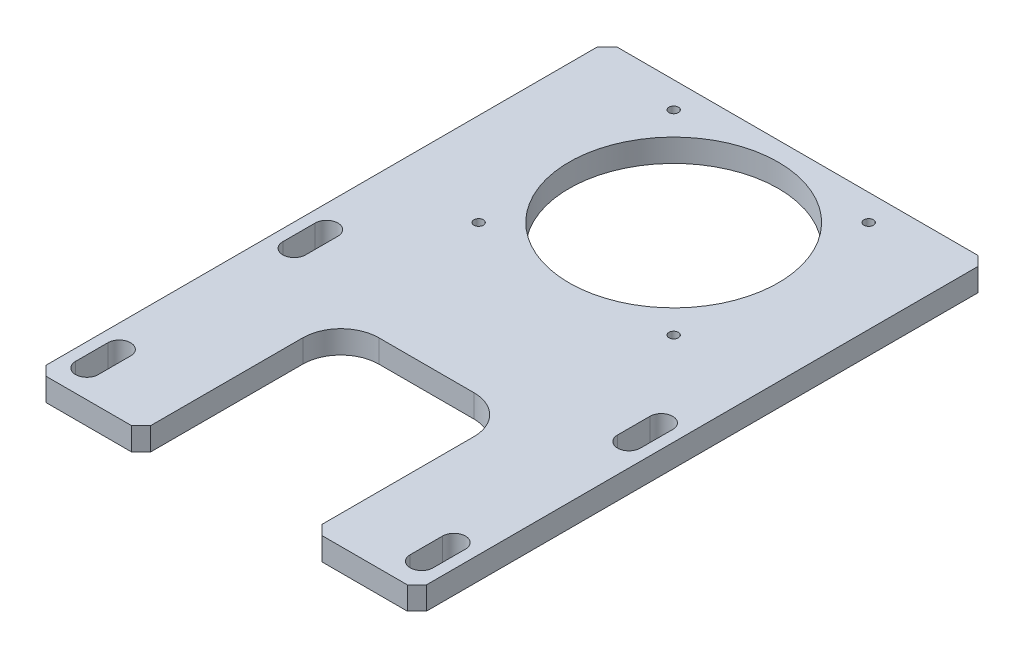
SolidWorks part; units mm, degrees
ref_plane "Front" through (0, 0, 0) normal (0, 0, 1) x (1, 0, 0)
ref_plane "Top" through (0, 0, 0) normal (0, 1, 0) x (1, 0, 0)
ref_plane "Right" through (0, 0, 0) normal (1, 0, 0) x (0, 0, -1)
sketch "Sketch1" plane through (0, 0, 0) normal (0, 1, 0) x (1, 0, 0)
  line L0 (0, 14.9989) -> (0, -319.3105) construction
  line L1 (-100, 0) -> (100, 0)
  line L2 (-100, 0) -> (-100, -300)
  line L3 (-100, -300) -> (100, -300)
  line L4 (100, 0) -> (100, -300)
  dimension "D1" = 200
  dimension "D2" = 300
extrude "Boss-Extrude1" add sketch "Sketch1" along normal blind 12
sketch "Sketch2" plane through (0, 12, 0) normal (0, 1, 0) x (1, 0, 0)
  line L0 (-100, -300) -> (100, -300) construction
  line L1 (-45, -195) -> (45, -195)
  line L2 (-45, -195) -> (-45, -300)
  line L3 (-45, -300) -> (45, -300)
  line L4 (45, -195) -> (45, -300)
  line L5 (0, 22.6259) -> (0, -270.9785) construction
  line L6 (100, 0) -> (-100, 0) construction
  dimension "D1" = 90
  dimension "D2" = 195
extrude "Cut-Extrude1" cut sketch "Sketch2" against normal up to next
sketch "Sketch3" plane through (0, 12, 0) normal (0, 1, 0) x (1, 0, 0)
  line L0 (100, 0) -> (-100, 0) construction
  circle A0 centre (0, -65) radius 55
  dimension "D1" = 110
  dimension "D2" = 65
extrude "Cut-Extrude2" cut sketch "Sketch3" against normal up to next
sketch "Sketch4" plane through (0, 12, 0) normal (0, 1, 0) x (1, 0, 0)
  line L0 (-88, -268.5) -> (-88, -285.5) construction
  line L1 (-82, -268.5) -> (-82, -285.5)
  line L2 (-94, -268.5) -> (-94, -285.5)
  line L3 (88, -268.5) -> (88, -285.5) construction
  line L4 (94, -268.5) -> (94, -285.5)
  line L5 (82, -268.5) -> (82, -285.5)
  line L6 (-88, -176.5) -> (-88, -159.5) construction
  line L7 (-94, -176.5) -> (-94, -159.5)
  line L8 (-82, -176.5) -> (-82, -159.5)
  line L9 (88, -176.5) -> (88, -159.5) construction
  line L10 (82, -176.5) -> (82, -159.5)
  line L11 (94, -176.5) -> (94, -159.5)
  line L12 (0, 33.6326) -> (0, -314.3435) construction
  line L13 (100, 0) -> (-100, 0) construction
  arc A0 (-82, -268.5) -> (-94, -268.5) centre (-88, -268.5) ccw
  arc A1 (-94, -285.5) -> (-82, -285.5) centre (-88, -285.5) ccw
  arc A2 (94, -268.5) -> (82, -268.5) centre (88, -268.5) ccw
  arc A3 (82, -285.5) -> (94, -285.5) centre (88, -285.5) ccw
  arc A4 (-94, -176.5) -> (-82, -176.5) centre (-88, -176.5) ccw
  arc A5 (-82, -159.5) -> (-94, -159.5) centre (-88, -159.5) ccw
  arc A6 (82, -176.5) -> (94, -176.5) centre (88, -176.5) ccw
  arc A7 (94, -159.5) -> (82, -159.5) centre (88, -159.5) ccw
  point P2 (-88, -277)
  point P7 (88, -277)
  point P14 (-88, -168)
  point P21 (88, -168)
  dimension "D1" = 109
  dimension "D2" = 176
  dimension "D3" = 17
  dimension "D4" = 168
  dimension "D5" = 12
extrude "Cut-Extrude3" cut sketch "Sketch4" against normal up to next
hole_wizard "M6x1.0 Tapped Hole1" positions "Sketch6" profile "Sketch7" tap size "M6x1.0" standard "JIS" end condition up to next
sketch "Sketch6" plane through (0, 12, 0) normal (0, 1, 0) x (-1, 0, 0)
  line L3 (0, 65) -> (72.5, 65) construction
  line L6 (0, 65) -> (51.2652, 116.2652) construction
  circle A0 centre (0, 65) radius 72.5 construction
  point P1 (-51.2652, 116.2652)
  point P3 (51.2652, 116.2652)
  point P5 (-51.2652, 13.7348)
  point P7 (51.2652, 13.7348)
  dimension "D1" = 145
  dimension "D2" = 45
sketch "Sketch7" plane through (51.2652, 12, 116.2652) normal (1, 0, 0) x (0, 0, 1)
  line L0 (0, 0) -> (0, 12)
  line L1 (0, 12) -> (2.5, 12)
  line L2 (2.5, 12) -> (2.5, 0)
  line L5 (2.5, 0) -> (0, 0)
  line L11 (0, -6.35) -> (0, 107.95) construction
  dimension "Thru Tap Drill Dia." = 5
  dimension "Thru Tap Drill Depth" = 12
cosmetic thread "Hole Thread1" parameters "D2"=6
cosmetic thread "Hole Thread2" parameters "D2"=6
cosmetic thread "Hole Thread3" parameters "D2"=6
cosmetic thread "Hole Thread4" parameters "D2"=6
fillet "Fillet1" radius 20 2 edges at (45, 6, 195) (-45, 6, 195)
chamfer "Chamfer1" distance 5 angle 45 6 edges at (-100, 6, 0) (100, 6, 0) (-100, 6, 300) (100, 6, 300) (45, 6, 300) (-45, 6, 300)
